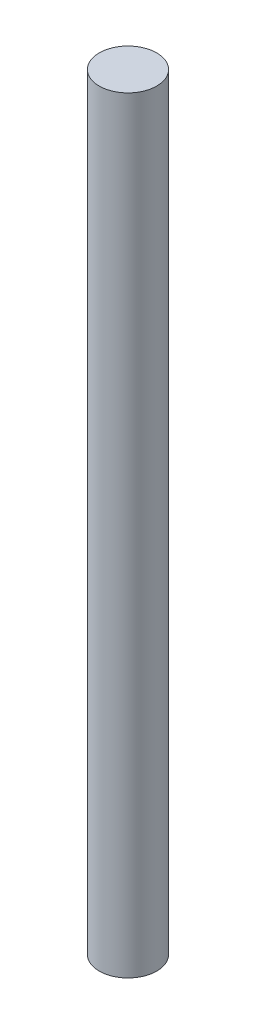
SolidWorks part; units mm, degrees
material "AISI 1010 Steel, hot rolled bar"
ref_plane "Front Plane" through (0, 0, 0) normal (0, 0, 1) x (1, 0, 0)
ref_plane "Top Plane" through (0, 0, 0) normal (0, 1, 0) x (1, 0, 0)
ref_plane "Right Plane" through (0, 0, 0) normal (1, 0, 0) x (0, 0, -1)
sketch "Sketch3" plane through (0, 0, 0) normal (0, 1, 0) x (1, 0, 0)
  circle A0 centre (0, 0) radius 9.525
  dimension "D1" = 19.05
extrude "Boss-Extrude1" add sketch "Sketch3" along normal blind 254
